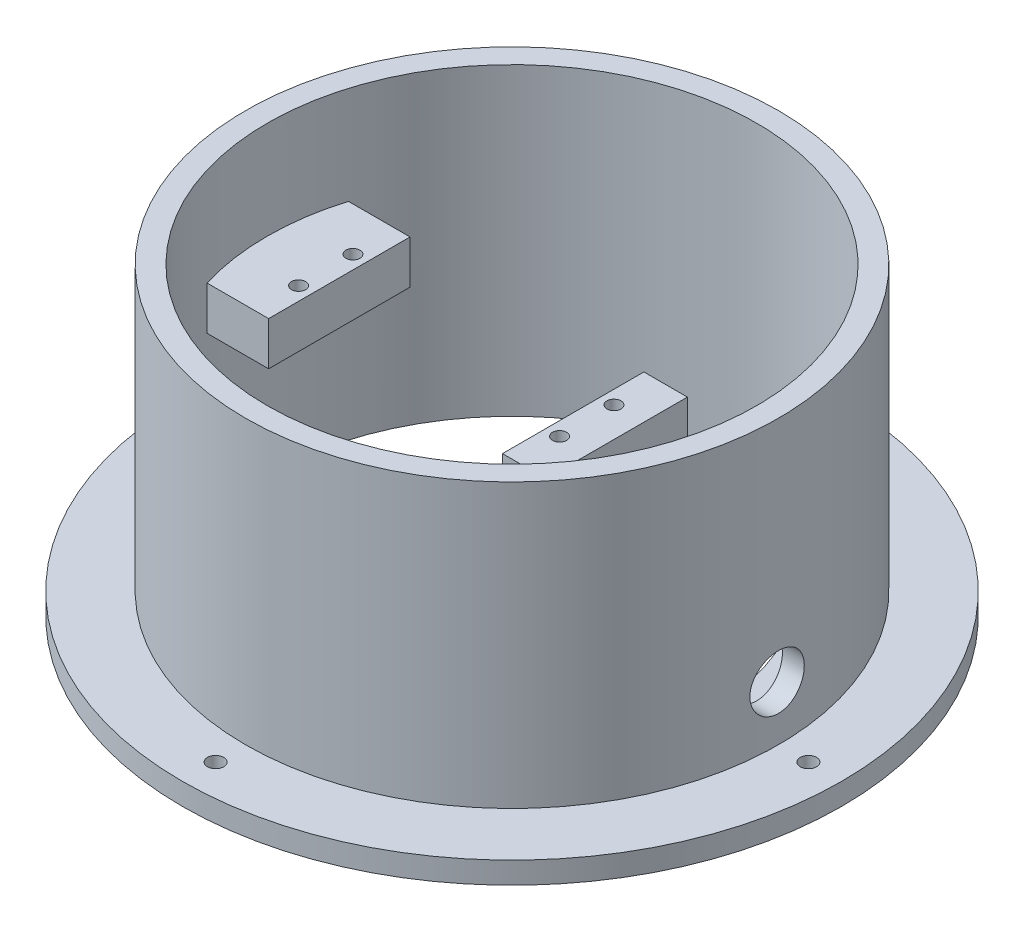
SolidWorks part; units mm, degrees
ref_plane "Front Plane" through (0, 0, 0) normal (0, 0, 1) x (1, 0, 0)
ref_plane "Top Plane" through (0, 0, 0) normal (0, 1, 0) x (1, 0, 0)
ref_plane "Right Plane" through (0, 0, 0) normal (1, 0, 0) x (0, 0, -1)
sketch "Sketch1" plane through (0, 0, 0) normal (0, 1, 0) x (1, 0, 0)
  circle A0 centre (0, 0) radius 45
  circle A1 centre (0, 0) radius 60.625
  dimension "D1" = 90
  dimension "D2" = 121.25
extrude "Boss-Extrude1" add sketch "Sketch1" along normal blind 4
sketch "Sketch2" plane through (0, 4, 0) normal (0, 1, 0) x (1, 0, 0)
  circle A0 centre (0, 0) radius 45
  circle A1 centre (0, 0) radius 49
  dimension "D1" = 90
  dimension "D2" = 98
extrude "Boss-Extrude2" add sketch "Sketch2" along normal blind 52
sketch "Sketch3" plane through (0, 0, 0) normal (0, 0, 1) x (1, 0, 0)
  line L0 (-60.625, 0) -> (60.625, 0) construction
  line L1 (11.25, 0) -> (19.25, 0)
  line L2 (11.25, 0) -> (11.25, 38)
  line L3 (11.25, 38) -> (19.25, 38)
  line L4 (19.25, 0) -> (19.25, 38)
  line L5 (45, 56) -> (-45, 56) construction
  line L6 (-46.75, 38) -> (-31.75, 38)
  line L7 (-46.75, 38) -> (-46.75, 30)
  line L8 (-46.75, 30) -> (-31.75, 30)
  line L9 (-31.75, 38) -> (-31.75, 30)
  dimension "D1" = 8
  dimension "D2" = 11.25
  dimension "D3" = 38
  dimension "D4" = 43
  dimension "D5" = 15
  dimension "D6" = 8
  dimension "D7" = 18
extrude "Boss-Extrude3" add sketch "Sketch3" along normal mid plane 26
sketch "Sketch4" plane through (11.25, 0, 0) normal (-1, 0, 0) x (0, 0, 1)
  line L0 (0, 0) -> (0, 56) construction
  line L1 (49, 56) -> (-49, 56) construction
  line L2 (-60.625, 0) -> (60.625, 0) construction
  line L3 (-5, 29) -> (5, 29)
  line L4 (-5, 29) -> (-5, 5)
  line L5 (-5, 5) -> (5, 5)
  line L6 (5, 29) -> (5, 5)
  line L7 (-5, 29) -> (5, 5) construction
  line L8 (-5, 5) -> (5, 29) construction
  point P5 (0, 17)
  dimension "D1" = 5
  dimension "D2" = 24
  dimension "D3" = 10
extrude "Cut-Extrude1" cut sketch "Sketch4" against normal up to next (8 mm away)
sketch "Sketch5" plane through (11.25, 0, 0) normal (-1, 0, 0) x (0, 0, 1)
  line L0 (0, 0) -> (0, 56) construction
  line L1 (49, 56) -> (-49, 56) construction
  line L2 (-60.625, 0) -> (60.625, 0) construction
  circle A0 centre (0, 14) radius 5
  dimension "D2" = 10
  dimension "D1" = 14
extrude "Cut-Extrude2" cut sketch "Sketch5" against normal through all
sketch "Sketch6" plane through (0, 38, 0) normal (0, 1, 0) x (1, 0, 0)
  line L0 (-45, 0) -> (49, 0) construction
  line L1 (-31.75, -13) -> (-31.75, 13) construction
  line L2 (-34.25, 5) -> (13.75, 5) construction
  line L3 (-34.25, 5) -> (-34.25, -5) construction
  line L4 (-34.25, -5) -> (13.75, -5) construction
  line L5 (13.75, 5) -> (13.75, -5) construction
  line L6 (11.25, -13) -> (11.25, 13) construction
  arc A0 (-43.0813, 13) -> (-43.0813, -13) centre (0, 0) ccw construction
  circle A1 centre (0, 0) radius 49 construction
  circle A2 centre (-34.25, 5) radius 1.3
  circle A3 centre (-34.25, -5) radius 1.3
  circle A4 centre (13.75, 5) radius 1.3
  circle A5 centre (13.75, -5) radius 1.3
  dimension "D5" = 2.6
  dimension "D1" = 5
  dimension "D2" = 5
  dimension "D3" = 2.5
  dimension "D4" = 2.5
extrude "Cut-Extrude3" cut sketch "Sketch6" against normal blind 7.2
sketch "Sketch7" plane through (0, 0, 0) normal (0, -1, 0) x (1, 0, 0)
  line L0 (11.25, 13) -> (25.2498, 37.2484)
  line L1 (19.25, 0) -> (66.4495, 0) construction
  line L2 (19.25, 13) -> (19.25, -13) construction
  line L3 (11.25, -13) -> (25.2498, -37.2484)
  line L4 (11.25, 13) -> (11.25, -13)
  line L5 (24.25, 19.5167) -> (27.3618, 24.9065)
  line L6 (24.25, -19.5167) -> (27.3618, -24.9065)
  line L8 (24.25, 19.5167) -> (24.25, -19.5167)
  line L9 (19.25, 10.8564) -> (27.3618, 24.9065) construction
  line L10 (19.25, 10.8564) -> (19.25, -10.8564) construction
  line L11 (19.25, -10.8564) -> (27.3618, -24.9065) construction
  circle A0 centre (0, 0) radius 45 construction
  arc A1 (25.2498, -37.2484) -> (25.2498, 37.2484) centre (0, 0) ccw
  arc A2 (27.3618, -24.9065) -> (27.3618, 24.9065) centre (0, 0) ccw
  dimension "D1" = 60
  dimension "D3" = 5
  dimension "D2" = 8
extrude "Boss-Extrude4" add sketch "Sketch7" against normal blind 4
sketch "Sketch8" plane through (0, 0, 0) normal (0, -1, 0) x (1, 0, 0)
  circle A0 centre (0, 0) radius 54.5 construction
  circle A1 centre (54.5, 0) radius 1.5
  circle A2 centre (0, -54.5) radius 1.5
  circle A3 centre (-54.5, 0) radius 1.5
  circle A4 centre (0, 54.5) radius 1.5
  dimension "D1" = 109
  dimension "D2" = 3
  dimension "D3" = 4
extrude "Cut-Extrude4" cut sketch "Sketch8" against normal through all
